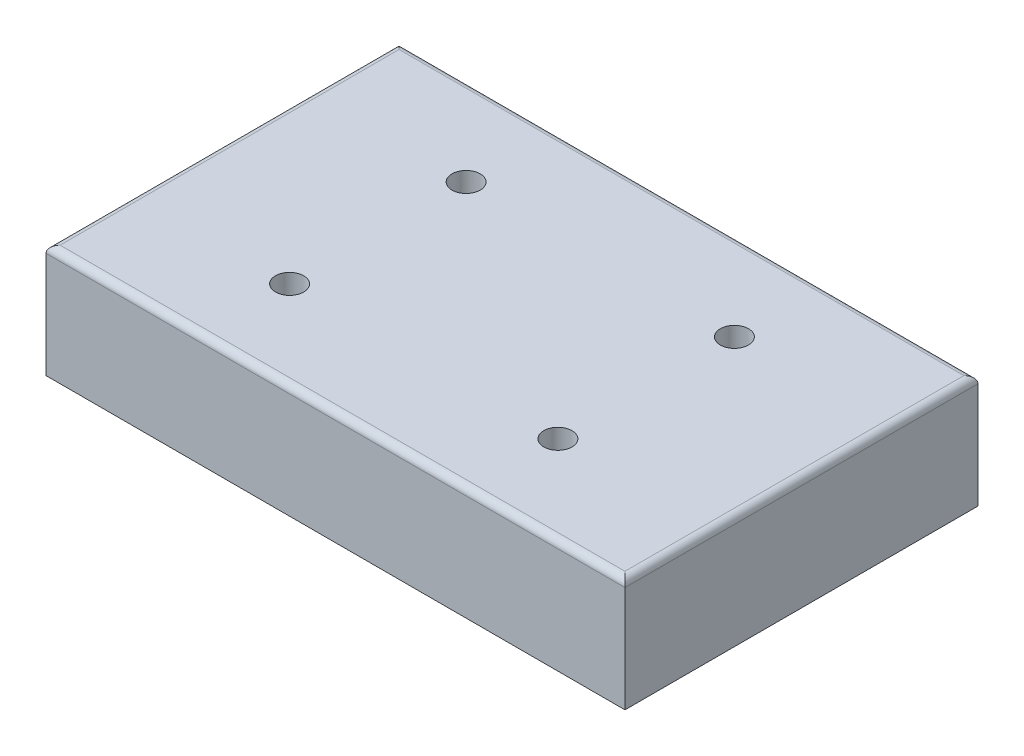
SolidWorks part; units mm, degrees
ref_plane "Front Plane" through (0, 0, 0) normal (0, 0, 1) x (1, 0, 0)
ref_plane "Top Plane" through (0, 0, 0) normal (0, 1, 0) x (1, 0, 0)
ref_plane "Right Plane" through (0, 0, 0) normal (1, 0, 0) x (0, 0, -1)
sketch "Sketch1" plane through (0, 0, 0) normal (0, 1, 0) x (1, 0, 0)
  line L1 (-41, 25) -> (41, 25)
  line L2 (-41, 25) -> (-41, -25)
  line L3 (-41, -25) -> (41, -25)
  line L4 (41, 25) -> (41, -25)
  line L5 (-41, 25) -> (41, -25) construction
  line L6 (-41, -25) -> (41, 25) construction
  point P0 (0, 0)
  dimension "D1" = 82
  dimension "D2" = 50
extrude "Boss-Extrude1" add sketch "Sketch1" along normal blind 16
fillet "Fillet1" radius 1 4 edges at (0, 16, 25) (41, 16, 0) (0, 16, -25) (-41, 16, 0)
sketch "Sketch2" plane through (0, 16, 0) normal (0, 1, 0) x (1, 0, 0)
  line L0 (0, 0) -> (0, 24) construction
  line L1 (40, 24) -> (-40, 24) construction
  line L2 (0, 0) -> (-40, 0) construction
  line L3 (-40, 24) -> (-40, -24) construction
sketch "Sketch7" plane through (0, 16, 0) normal (0, 1, 0) x (1, 0, 0)
  line L0 (0, 0) -> (0, 24) construction
  line L3 (0, 0) -> (-40, 0) construction
  point P0 (-19, 12.5)
  point P5 (19, 12.5)
  point P10 (19, -12.5)
  point P11 (-19, -12.5)
  dimension "D1" = 19
  dimension "D2" = 12.5
hole_wizard "Ø4.0 (4) Diameter Hole3" positions "Sketch10" profile "Sketch11" hole size "Ø4.0" standard "ISO"
sketch "Sketch10" plane through (0, 16, 0) normal (0, 1, 0) x (1, 0, 0)
  point P0 (-19, 12.5)
  point P3 (19, 12.5)
  point P6 (19, -12.5)
  point P9 (-19, -12.5)
sketch "Sketch11" plane through (-19, 16, -12.5) normal (1, 0, 0) x (0, 0, 1)
  line L0 (0, 0) -> (0, 8)
  line L1 (0, 8) -> (2, 6.7983)
  line L2 (2, 6.7983) -> (2, 0)
  line L5 (2, 0) -> (0, 0)
  line L10 (0, 8) -> (-2, 6.7983) construction
  line L11 (0, -6.35) -> (0, 107.95) construction
  dimension "Hole Dia." = 4
  dimension "Hole Depth" = 8
  dimension "Drill Angle" = 118
